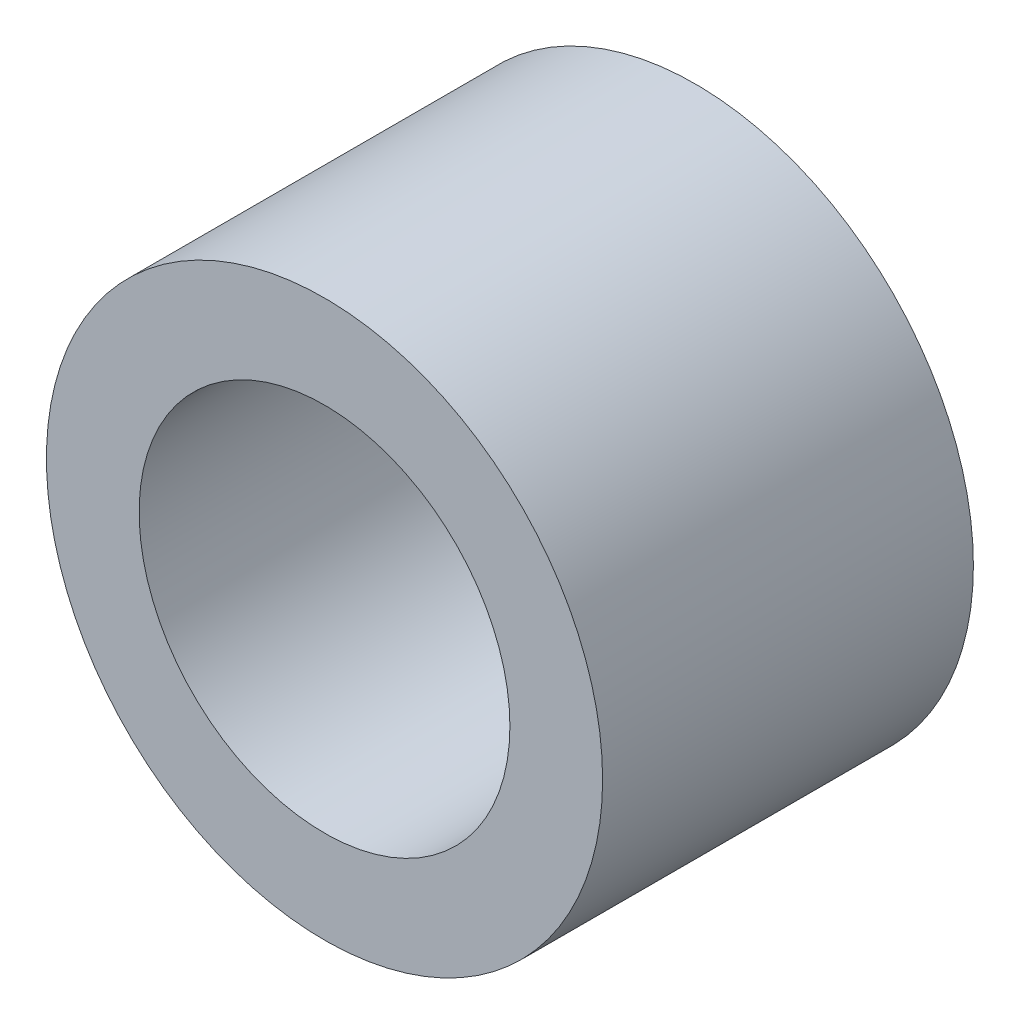
SolidWorks part; units mm, degrees
material "1.3505 (100Cr6) hardened 60 HRC"
ref_plane "Front Plane" through (0, 0, 0) normal (0, 0, 1) x (1, 0, 0)
ref_plane "Top Plane" through (0, 0, 0) normal (0, 1, 0) x (1, 0, 0)
ref_plane "Right Plane" through (0, 0, 0) normal (1, 0, 0) x (0, 0, -1)
sketch "Sketch1" plane through (0, 0, 0) normal (0, 0, 1) x (1, 0, 0)
  circle A0 centre (0, 0) radius 6
  circle A1 centre (0, 0) radius 9
  dimension "D1" = 12
  dimension "D2" = 18
extrude "EX_Bearing_Envelope_12mm" add sketch "Sketch1" along normal mid plane 12
